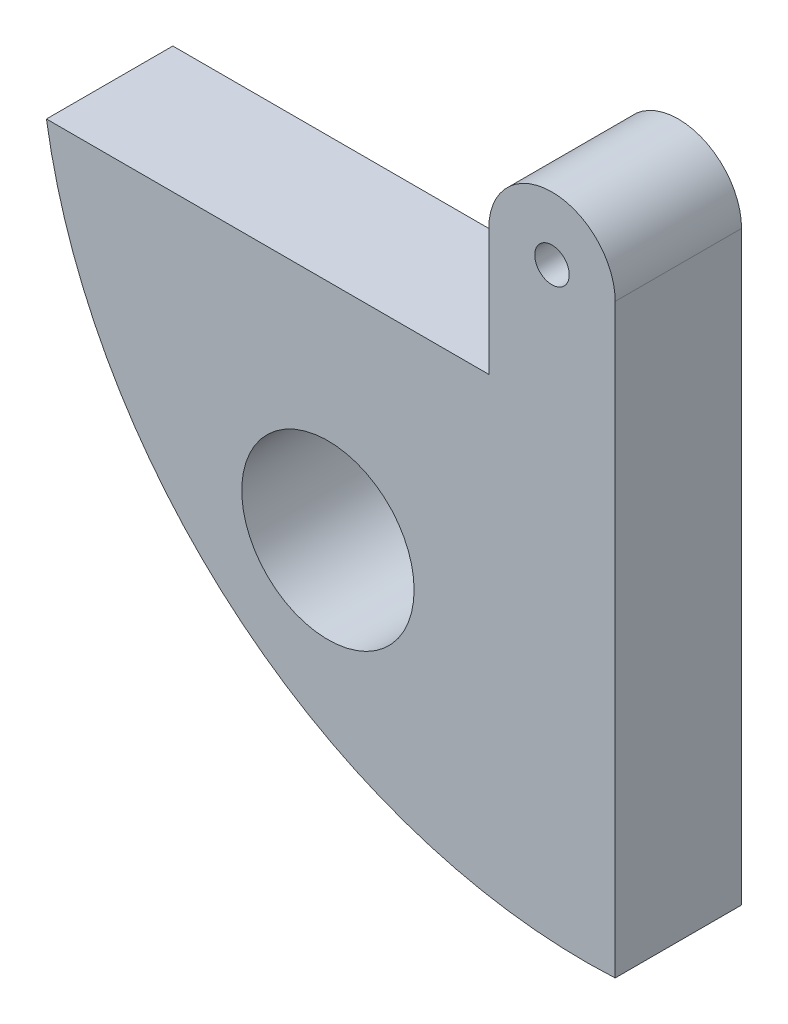
SolidWorks part; units mm, degrees
ref_plane "Plan de face" through (0, 0, 0) normal (0, 0, 1) x (1, 0, 0)
ref_plane "Plan de dessus" through (0, 0, 0) normal (0, 1, 0) x (1, 0, 0)
ref_plane "Plan de droite" through (0, 0, 0) normal (1, 0, 0) x (0, 0, -1)
sketch "Esquisse1" plane through (0, 0, 0) normal (0, 0, 1) x (1, 0, 0)
  line L0 (0, 0) -> (0, 72) construction
  line L1 (0, 72) -> (-22, 72) construction
  line L2 (-22, 72) -> (-22, 39) construction
  line L3 (-22, 39) -> (-50, 39) construction
  line L4 (0, 0) -> (0, 61)
  line L5 (-22, 39) -> (-22, 61)
  line L6 (-50, 39) -> (-50, 0) construction
  line L7 (-50, 39) -> (-148, 39) construction
  line L8 (0, 72) -> (0, -8) construction
  line L9 (-104.8282, 39) -> (-104.8282, -41) construction
  line L10 (-104.8282, -41) -> (0, -41) construction
  line L11 (0, 0) -> (0, -41)
  line L12 (-22, 39) -> (-99, 39)
  arc A0 (-22, 61) -> (0, 61) centre (-11, 61) cw
  circle A1 centre (-50, 0) radius 15
  arc A2 (0, -41) -> (-99, 39) centre (-5.1693, 53.8593) cw
  circle A3 centre (-11, 61) radius 3
  dimension "D6" = 30
  dimension "D7" = 80
  dimension "D8" = 6
  dimension "D9" = 95
  dimension "D1" = 72
  dimension "D2" = 22
  dimension "D3" = 33
  dimension "D4" = 28
  dimension "D5" = 61
  dimension "D10" = 77
extrude "Boss.-Extru.3" add sketch "Esquisse1" along normal blind 22
